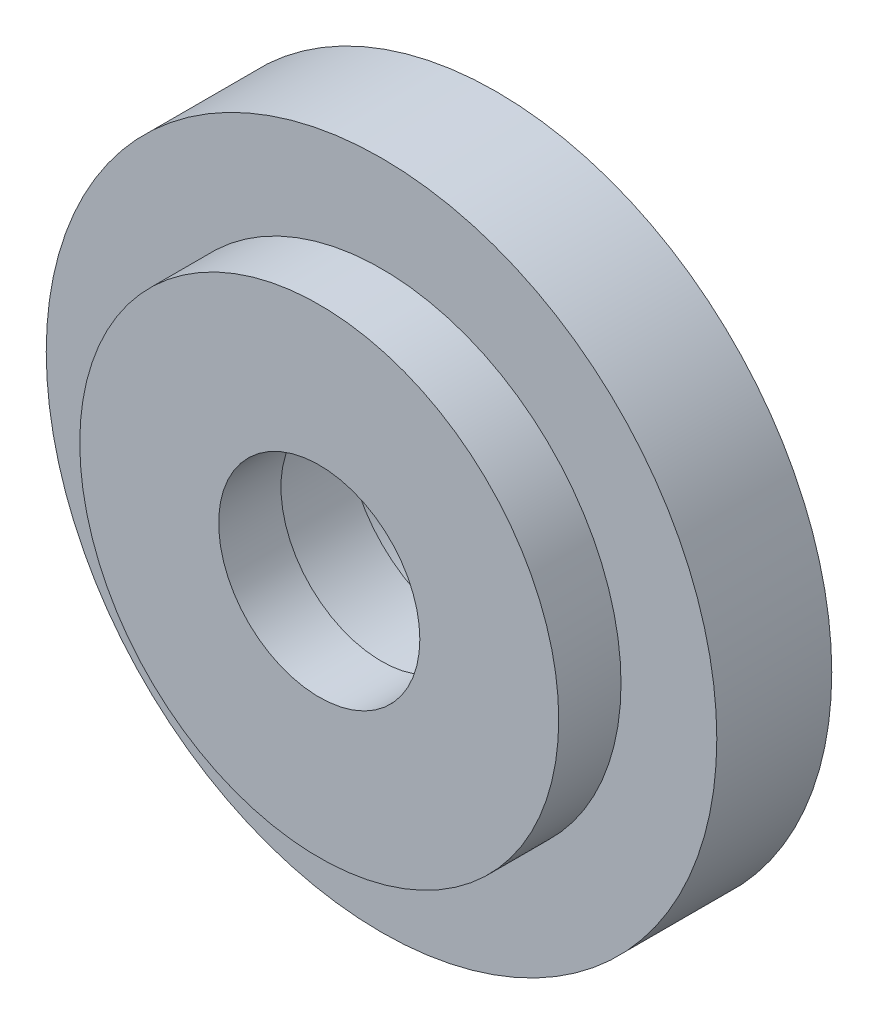
SolidWorks part; units mm, degrees
ref_plane "Front Plane" through (0, 0, 0) normal (0, 0, 1) x (1, 0, 0)
ref_plane "Top Plane" through (0, 0, 0) normal (0, 1, 0) x (1, 0, 0)
ref_plane "Right Plane" through (0, 0, 0) normal (1, 0, 0) x (0, 0, -1)
sketch "Sketch1" plane through (0, 0, 0) normal (0, 0, 1) x (1, 0, 0)
  circle A1 centre (0, 0) radius 12.7
  dimension "D2" = 25.4
extrude "Boss-Extrude1" add sketch "Sketch1" along normal blind 12.7
ref_plane "Plane1" through (0, 0, 6.35) normal (0, 0, 1) x (1, 0, 0)
sketch "Sketch2" plane through (0, 0, 6.35) normal (0, 0, 1) x (1, 0, 0)
  circle A2 centre (0, 0) radius 17.78
  dimension "D1" = 35.56
extrude "Boss-Extrude2" add sketch "Sketch2" along normal mid plane 6.096
sketch "Sketch5" plane through (0, 0, 0) normal (0, 0, -1) x (-1, 0, 0)
  circle A0 centre (0, 0) radius 6.4135
  dimension "D1" = 12.827
extrude "Cut-Extrude1" cut sketch "Sketch5" against normal up to surface (9.398 mm away) up to face at (12.7, 0, 9.398)
sketch "Sketch6" plane through (0, 0, 12.7) normal (0, 0, 1) x (1, 0, 0)
  circle A0 centre (0, 0) radius 5.334
  dimension "D1" = 10.668
extrude "Cut-Extrude2" cut sketch "Sketch6" against normal through all
sketch "Sketch7" plane through (0, 0, 0) normal (0, 0, -1) x (-1, 0, 0)
  circle A0 centre (0, 0) radius 8.255
  dimension "D1" = 16.51
extrude "Cut-Extrude3" cut sketch "Sketch7" against normal offset from surface (4.826 mm away) 4.572 up to face at (5.334, 0, 9.398)
